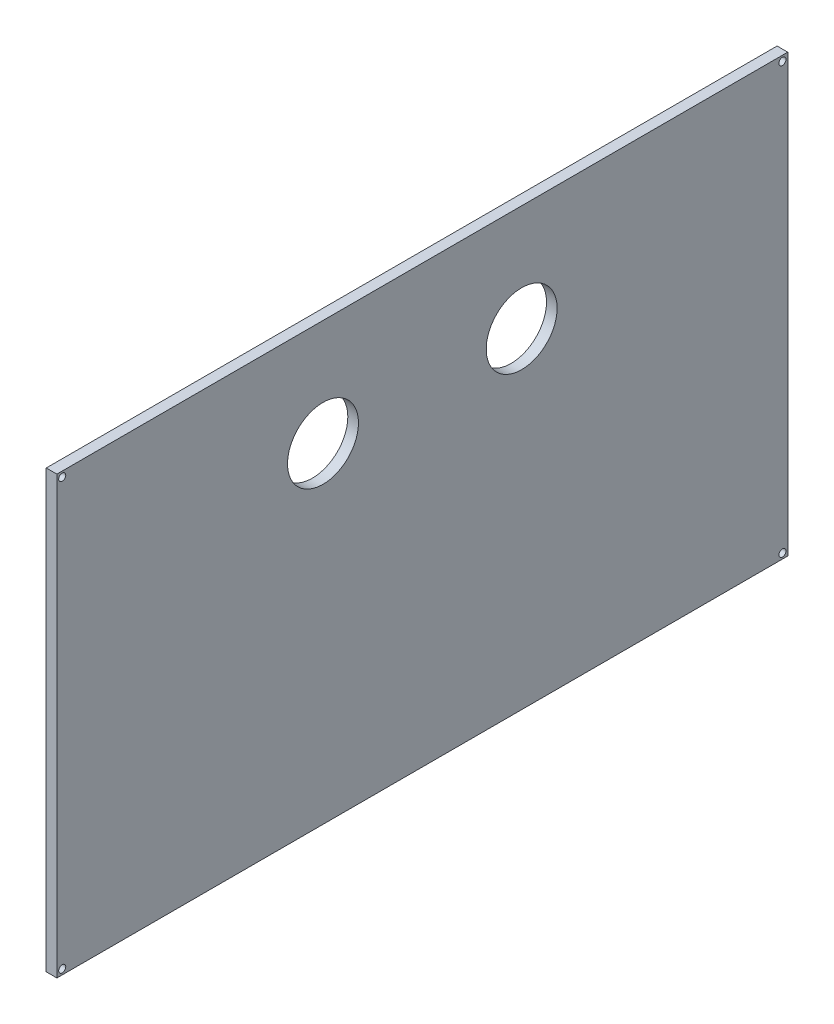
SolidWorks part; units mm, degrees
ref_plane "Front Plane" through (0, 0, 0) normal (0, 0, 1) x (1, 0, 0)
ref_plane "Top Plane" through (0, 0, 0) normal (0, 1, 0) x (1, 0, 0)
ref_plane "Right Plane" through (0, 0, 0) normal (1, 0, 0) x (0, 0, -1)
sketch "Sketch1" plane through (0, 0, 0) normal (1, 0, 0) x (0, 0, -1)
  line L1 (0, 0) -> (206, 0)
  line L2 (0, 0) -> (0, 123)
  line L3 (0, 123) -> (206, 123)
  line L4 (206, 0) -> (206, 123)
  circle A0 centre (75, 93) radius 10
  circle A1 centre (131, 93) radius 10
  circle A2 centre (204.5, 1.5) radius 1
  circle A3 centre (1.5, 1.5) radius 1
  circle A4 centre (204.5, 121.5) radius 1
  circle A5 centre (1.5, 121.5) radius 1
  dimension "D5" = 20
  dimension "D6" = 20
  dimension "D9" = 2
  dimension "D14" = 2
  dimension "D17" = 2
  dimension "D20" = 2
  dimension "D1" = 123
  dimension "D2" = 206
  dimension "D3" = 30
  dimension "D4" = 30
  dimension "D7" = 75
  dimension "D8" = 75
  dimension "D10" = 1.5
  dimension "D11" = 1.5
  dimension "D12" = 1.5
  dimension "D13" = 1.5
  dimension "D15" = 1.5
  dimension "D16" = 1.5
  dimension "D18" = 1.5
  dimension "D19" = 1.5
extrude "Boss-Extrude1" add sketch "Sketch1" along normal blind 3
